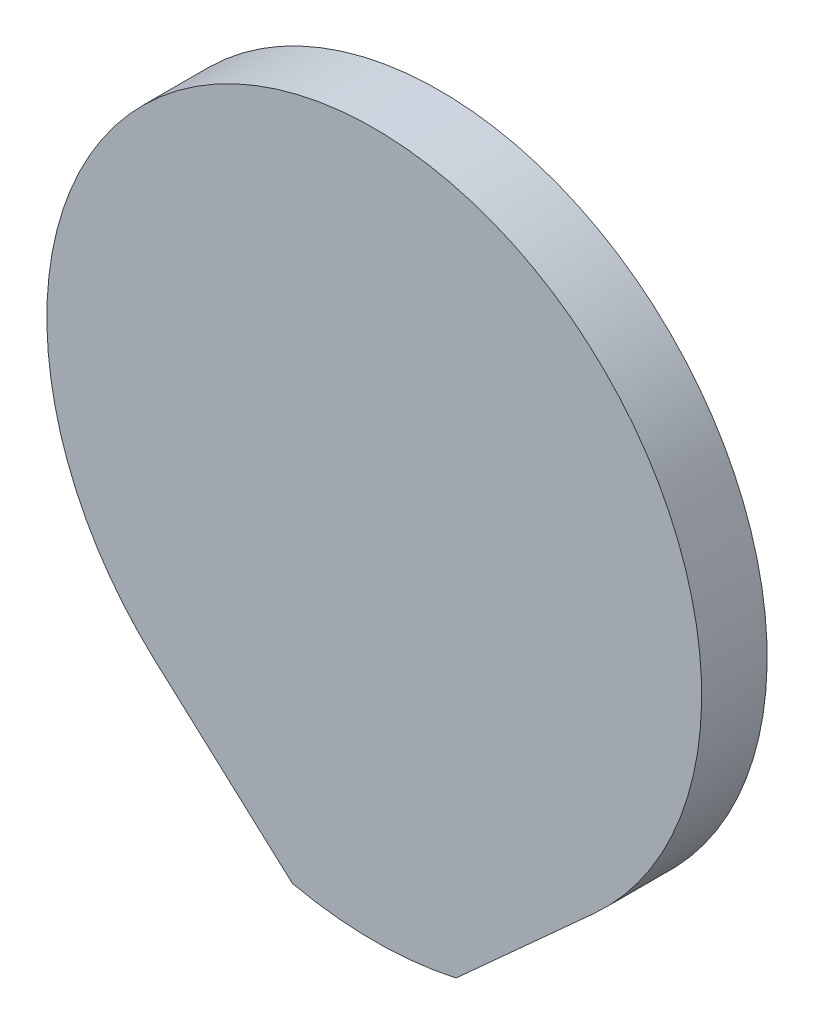
SolidWorks part; units mm, degrees
material "ABS"
ref_plane "前基準面" through (0, 0, 0) normal (0, 0, 1) x (1, 0, 0)
ref_plane "上基準面" through (0, 0, 0) normal (0, 1, 0) x (1, 0, 0)
ref_plane "右基準面" through (0, 0, 0) normal (1, 0, 0) x (0, 0, -1)
sketch "草圖1" plane through (0, 0, 0) normal (0, 0, 1) x (1, 0, 0)
  line L0 (0, 0) -> (0, -230)
  line L1 (50, -224.4994) -> (134.2088, -148.2835)
  line L3 (-50, -224.4994) -> (-134.2088, -148.2835)
  arc A0 (134.2088, -148.2835) -> (-134.2088, -148.2835) centre (0, 0) ccw
  arc A1 (-50, -224.4994) -> (50, -224.4994) centre (0, 0) ccw
  dimension "D1" = 230
  dimension "D2" = 400
  dimension "D3" = 460
  dimension "D4" = 50
  dimension "D5" = 50
extrude "填料-伸長1" add sketch "草圖1" along normal blind 40
